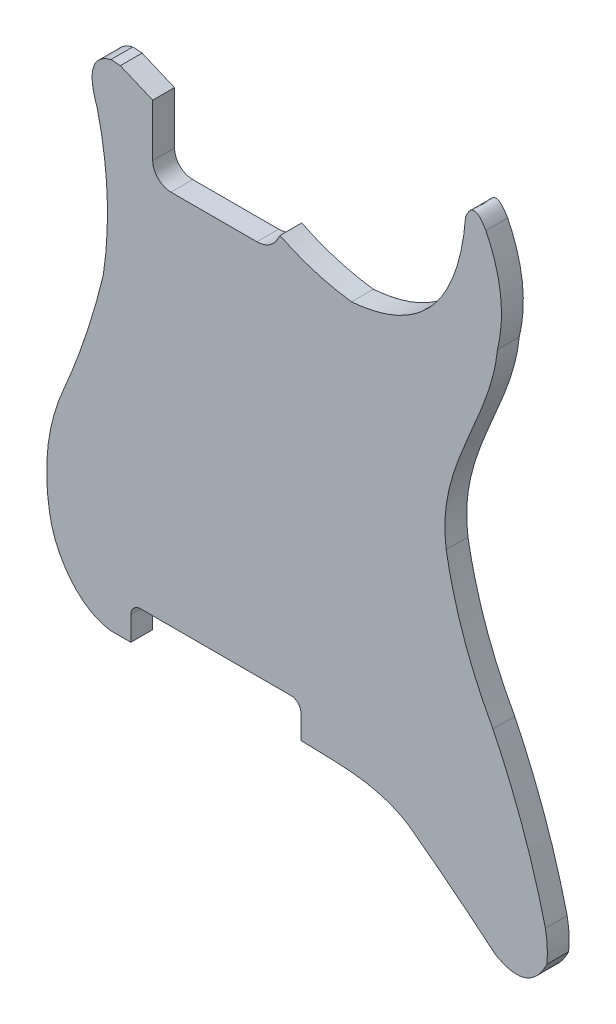
SolidWorks part; units mm, degrees
ref_plane "Front Plane" through (0, 0, 0) normal (0, 0, 1) x (1, 0, 0)
ref_plane "Top Plane" through (0, 0, 0) normal (0, 1, 0) x (1, 0, 0)
ref_plane "Right Plane" through (0, 0, 0) normal (1, 0, 0) x (0, 0, -1)
sketch "Sketch2" plane through (0, 0, 0) normal (0, 0, 1) x (1, 0, 0)
  line L0 (37.7963, 136.0288) -> (188.9817, 136.0288) construction
  line L1 (-24.4354, 135.9031) -> (114.0666, 135.9031) construction
  line L2 (48.3869, 158.6685) -> (241.9346, 158.6685) construction
  line L3 (124.6413, 54.5796) -> (124.6413, 65.5767)
  line L4 (120.0753, 70.1427) -> (51.2124, 70.1427)
  line L5 (46.6464, 65.5767) -> (46.6464, 54.5796)
  line L6 (41.8207, 281.1825) -> (56.6782, 274.9115)
  line L7 (115.0461, 250.3595) -> (113.7797, 248.0703)
  line L8 (104.4571, 242.5736) -> (65.0492, 242.5736)
  line L9 (56.6782, 250.9446) -> (56.6782, 274.9115)
  arc A0 (124.6413, 65.5767) -> (120.0753, 70.1427) centre (120.0753, 65.5767) ccw
  arc A1 (51.2124, 70.1427) -> (46.6464, 65.5767) centre (51.2124, 65.5767) ccw
  arc A2 (113.7797, 248.0703) -> (104.4571, 242.5736) centre (104.4571, 253.2276) cw
  arc A3 (65.0492, 242.5736) -> (56.6782, 250.9446) centre (65.0492, 250.9446) cw
  spline S0 degree 2 poles (115.0461, 250.3595) (130.6415, 242.6032) (147.8629, 240.4198) knots 0 0 0 1 1 1
  spline S1 degree 2 poles (147.8629, 240.4198) (195.5843, 244.3684) (200.1786, 300.2998) knots 0 0 0 1 1 1
  spline S2 degree 2 poles (200.1786, 300.2998) (203.7877, 309.5318) (209.4793, 299.5155) knots 0 0 0 1 1 1
  spline S3 degree 2 poles (209.4793, 299.5155) (220.3199, 277.4496) (214.7534, 254.8099) knots 0 0 0 1 1 1
  spline S4 degree 3 poles (214.7534, 254.8099) (211.6228, 223.2104) (186.431, 197.6476) (191.264, 163.6913) knots 0 0 0 0 1 1 1 1
  spline S5 degree 2 poles (191.264, 163.6913) (196.8547, 131.7261) (212.6991, 103.2382) knots 0 0 0 1 1 1
  spline S6 degree 2 poles (212.6991, 103.2382) (228.3535, 71.0318) (236.7519, 36.0508) knots 0 0 0 1 1 1
  spline S7 degree 2 poles (236.7519, 36.0508) (238.175, 29.0488) (237.4272, 22.0751) knots 0 0 0 1 1 1
  spline S8 degree 2 poles (237.4272, 22.0751) (229.2983, 5.512) (213.9903, 14.0415) knots 0 0 0 1 1 1
  spline S9 degree 2 poles (213.9903, 14.0415) (194.6662, 30.3344) (174.3695, 45.3949) knots 0 0 0 1 1 1
  spline S10 degree 3 poles (174.3695, 45.3949) (159.8061, 55.0781) (141.1988, 53.9222) (124.6413, 54.5796) knots 0 0 0 0 1 1 1 1
  spline S11 degree 1 poles (46.6464, 54.5796) (37.5223, 54.5796) knots 0 0 1 1
  spline S12 degree 3 poles (37.5223, 54.5796) (21.9595, 56.5134) (11.2932, 73.6724) (9.3332, 87.8516) knots 0 0 0 0 1 1 1 1
  spline S13 degree 2 poles (9.3332, 87.8516) (4.8169, 115.1232) (16.1488, 140.4126) knots 0 0 0 1 1 1
  spline S14 degree 2 poles (16.1488, 140.4126) (27.4059, 166.5304) (34.0318, 194.2141) knots 0 0 0 1 1 1
  spline S15 degree 2 poles (34.0318, 194.2141) (38.9228, 226.8323) (31.2957, 258.8639) knots 0 0 0 1 1 1
  spline S16 degree 2 poles (31.2957, 258.8639) (24.3422, 277.969) (37.5223, 281.4822) knots 0 0 0 1 1 1
  spline S17 degree 1 poles (37.5223, 281.4822) (41.8207, 281.1825) knots 0 0 1 1
  point P53 (0, 0)
  point P59 (65.0492, 242.5736)
  point P60 (0, 0)
  point P61 (0, 0)
  dimension "D1" = 4.566
  dimension "D2" = 10.654
  dimension "D3" = 8.371
extrude "Boss-Extrude1" add sketch "Sketch2" along normal blind 10
